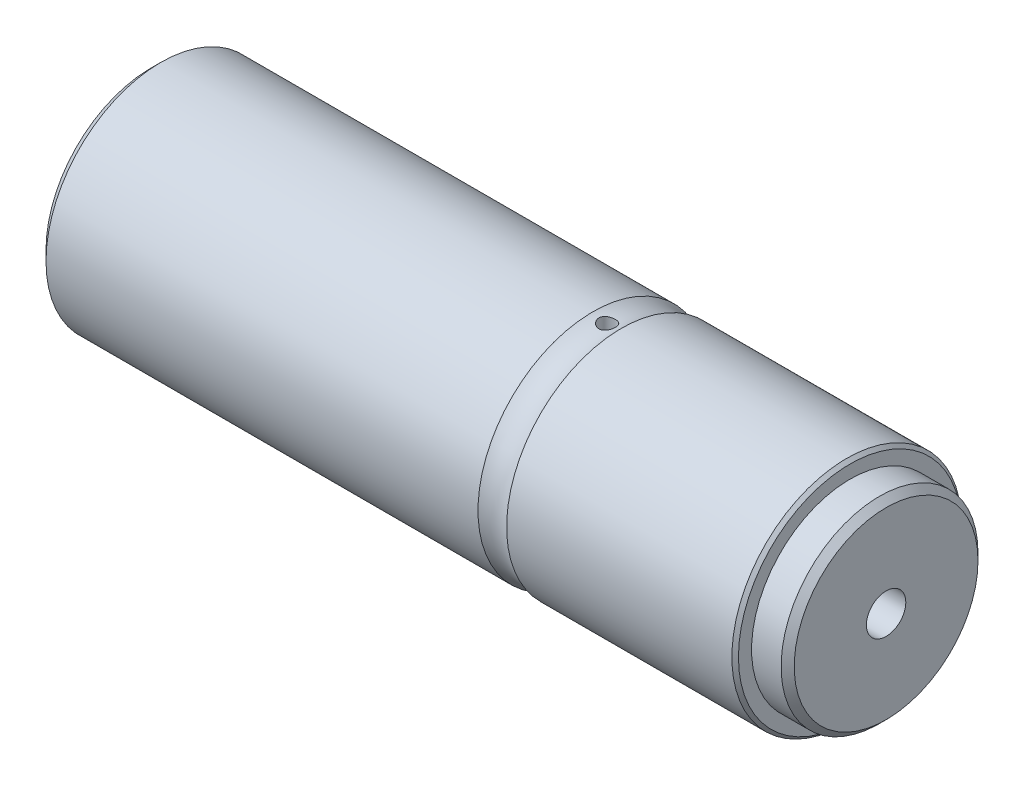
SolidWorks part; units mm, degrees
material "45"
ref_plane "前视基准面" through (0, 0, 0) normal (0, 0, 1) x (1, 0, 0)
ref_plane "上视基准面" through (0, 0, 0) normal (0, 1, 0) x (1, 0, 0)
ref_plane "右视基准面" through (0, 0, 0) normal (1, 0, 0) x (0, 0, -1)
sketch "草图1" plane through (0, 0, 0) normal (0, 0, 1) x (1, 0, 0)
  line L0 (0, 0) -> (-223.6223, 0) construction
  line L1 (0, 0) -> (0, 30)
  line L2 (0, 30) -> (-11, 30)
  line L3 (-11, 30) -> (-11, 35)
  line L4 (-11, 35) -> (-80.6411, 35)
  line L5 (-89.3589, 35) -> (-224, 35)
  line L6 (-224, 35) -> (-224, 0)
  line L7 (-224, 0) -> (0, 0)
  arc A0 (-80.6411, 35) -> (-89.3589, 35) centre (-85, 44) cw
  dimension "D1" = 60
  dimension "D5" = 10
  dimension "D2" = 70
  dimension "D3" = 11
  dimension "D4" = 85
  dimension "D6" = 224
  dimension "D7" = 9
revolve "旋转1" add sketch "草图1" angle 360 about L0
chamfer "倒角1" distance 3 angle 45 1 edges at (-224, 0, -35)
chamfer "倒角2" distance 2 angle 45 1 edges at (0, 0, -30)
chamfer "倒角3" distance 1 angle 45 1 edges at (-11, 0, -35)
sketch "草图2" plane through (0, 0, 0) normal (0, 1, 0) x (1, 0, 0)
  line L0 (0, 0) -> (-226.4394, 0) construction
  line L1 (0, -28) -> (0, 28) construction
  circle A0 centre (-85, 0) radius 2.5
  dimension "D1" = 5
  dimension "D2" = 85
extrude "切除-拉伸1" cut sketch "草图2" against normal mid plane 100
hole_wizard "Ø8.0 (8) 直径孔1" positions "3D草图1" profile "草图3" hole size "Ø8.0" standard "GB"
sketch3d "3D草图1"
  point P0 (0, 0, 0)
  point P4 (0, 0, 0)
sketch "草图3" plane through (0, 0, 0) normal (0, 1, 0) x (0, 0, -1)
  line L0 (0, 0) -> (0, 92.4034)
  line L1 (0, 92.4034) -> (4, 90)
  line L2 (4, 90) -> (4, 0)
  line L5 (4, 0) -> (0, 0)
  line L10 (0, 92.4034) -> (-4, 90) construction
  line L11 (0, -6.35) -> (0, 107.95) construction
  dimension "孔直径" = 8
  dimension "孔深度" = 90
  dimension "导头角度" = 118
hole_wizard "M14 螺纹孔1" positions "3D草图2" profile "草图4" tap size "M14" standard "GB"
sketch3d "3D草图2"
  point P0 (0, 0, 0)
  point P3 (0, 0, 0)
cosmetic thread "孔螺蚊线1" parameters "D1"=35, "D2"=14
cosmetic thread "孔螺蚊线2" parameters "D1"=35, "D2"=14
sketch "草图4" plane through (0, 0, 0) normal (0, 1, 0) x (0, 0, -1)
  line L0 (0, 0) -> (0, 48.6052)
  line L1 (0, 48.6052) -> (6, 45)
  line L2 (6, 45) -> (6, 0)
  line L5 (6, 0) -> (0, 0)
  line L10 (0, 48.6052) -> (-6, 45) construction
  line L11 (0, -6.35) -> (0, 107.95) construction
  dimension "螺纹孔钻头直径" = 12
  dimension "螺纹孔钻头深度" = 45
  dimension "导头角度" = 118
